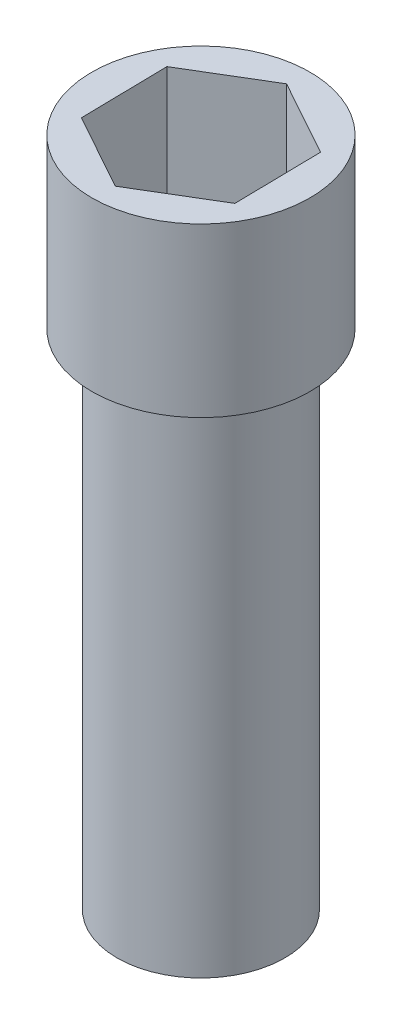
SolidWorks part; units mm, degrees
material "Alloy Steel"
ref_plane "Front Plane" through (0, 0, 0) normal (0, 0, 1) x (1, 0, 0)
ref_plane "Top Plane" through (0, 0, 0) normal (0, 1, 0) x (1, 0, 0)
ref_plane "Right Plane" through (0, 0, 0) normal (1, 0, 0) x (0, 0, -1)
sketch "Sketch1" plane through (0, 0, 0) normal (0, 1, 0) x (1, 0, 0)
  circle A0 centre (0, 0) radius 5
  dimension "D1" = 10
extrude "Boss-Extrude1" add sketch "Sketch1" along normal blind 30
sketch "Sketch2" plane through (0, 30, 0) normal (0, 1, 0) x (1, 0, 0)
  circle A0 centre (0, 0) radius 6.5
  dimension "D1" = 13
extrude "Boss-Extrude2" add sketch "Sketch2" along normal blind 10
sketch "Sketch3" plane through (0, 40, 0) normal (0, 1, 0) x (1, 0, 0)
  line L1 (4.5445, -2.5193) -> (4.4541, 2.676)
  line L2 (4.4541, 2.676) -> (-0.0905, 5.1954)
  line L3 (-0.0905, 5.1954) -> (-4.5445, 2.5193)
  line L4 (-4.5445, 2.5193) -> (-4.4541, -2.676)
  line L5 (-4.4541, -2.676) -> (0.0905, -5.1954)
  line L6 (0.0905, -5.1954) -> (4.5445, -2.5193)
  circle A0 centre (0, 0) radius 4.5 construction
  dimension "D1" = 9
extrude "Cut-Extrude1" cut sketch "Sketch3" against normal blind 9.5
